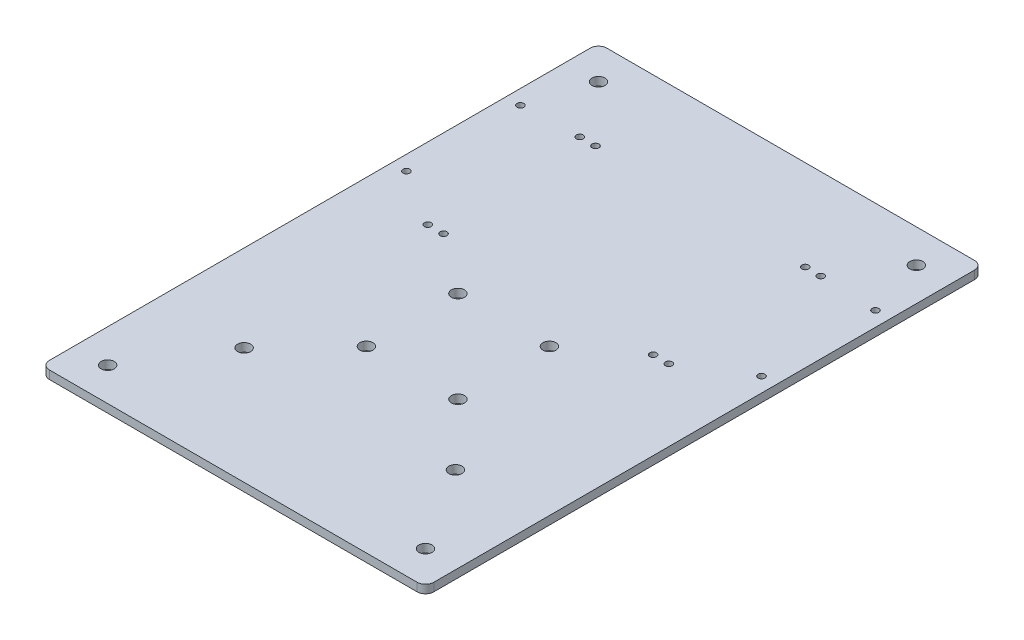
SolidWorks part; units mm, degrees
ref_plane "Front Plane" through (0, 0, 0) normal (0, 0, 1) x (1, 0, 0)
ref_plane "Top Plane" through (0, 0, 0) normal (0, 1, 0) x (1, 0, 0)
ref_plane "Right Plane" through (0, 0, 0) normal (1, 0, 0) x (0, 0, -1)
sketch "Sketch1" plane through (0, 0, 0) normal (0, 1, 0) x (1, 0, 0)
  line L1 (-60.6425, -93.6625) -> (60.6425, -93.6625) construction
  line L2 (-60.6425, -93.6625) -> (-60.6425, 93.6625) construction
  line L3 (-60.6425, 93.6625) -> (60.6425, 93.6625) construction
  line L4 (60.6425, -93.6625) -> (60.6425, 93.6625) construction
  line L5 (-60.6425, -93.6625) -> (60.6425, 93.6625) construction
  line L6 (-60.6425, 93.6625) -> (60.6425, -93.6625) construction
  line L7 (-73.3425, -106.3625) -> (73.3425, -106.3625)
  line L8 (-73.3425, -106.3625) -> (-73.3425, 106.3625)
  line L9 (-73.3425, 106.3625) -> (73.3425, 106.3625)
  line L10 (73.3425, -106.3625) -> (73.3425, 106.3625)
  line L11 (-73.3425, -106.3625) -> (73.3425, 106.3625) construction
  line L12 (-73.3425, 106.3625) -> (73.3425, -106.3625) construction
  circle A0 centre (-60.6425, 93.6625) radius 2.4892
  circle A1 centre (60.6425, 93.6625) radius 2.4892
  circle A2 centre (60.6425, -93.6625) radius 2.4892
  circle A3 centre (-60.6425, -93.6625) radius 2.4892
  point P0 (0, 0)
  point P11 (0, 0)
  dimension "D1" = 4.9784
  dimension "D2" = 121.285
  dimension "D3" = 187.325
  dimension "D4" = 12.7
  dimension "D5" = 12.7
extrude "Boss-Extrude1" add sketch "Sketch1" along normal mid plane 3.175
fillet "Fillet1" radius 3.175 4 edges at (-73.3425, 0, 106.3625) (-73.3425, 0, -106.3625) (73.3425, 0, -106.3625) (73.3425, 0, 106.3625)
sketch "Sketch2" plane through (0, 1.5875, 0) normal (0, 1, 0) x (1, 0, 0)
  line L1 (-46, 13.8625) -> (46, 13.8625) construction
  line L2 (-46, 13.8625) -> (-46, 71.8625) construction
  line L3 (-46, 71.8625) -> (46, 71.8625) construction
  line L4 (46, 13.8625) -> (46, 71.8625) construction
  line L5 (-46, 13.8625) -> (46, 71.8625) construction
  line L6 (-46, 71.8625) -> (46, 13.8625) construction
  line L7 (70.1675, 106.3625) -> (-70.1675, 106.3625) construction
  line L9 (-40, 13.8625) -> (40, 13.8625) construction
  line L10 (-40, 13.8625) -> (-40, 71.8625) construction
  line L11 (-40, 71.8625) -> (40, 71.8625) construction
  line L12 (40, 13.8625) -> (40, 71.8625) construction
  line L13 (-40, 13.8625) -> (40, 71.8625) construction
  line L14 (-40, 71.8625) -> (40, 13.8625) construction
  circle A0 centre (-46, 71.8625) radius 1.3
  circle A1 centre (-46, 13.8625) radius 1.3
  circle A2 centre (46, 71.8625) radius 1.3
  circle A3 centre (46, 13.8625) radius 1.3
  circle A4 centre (-40, 71.8625) radius 1.3
  circle A5 centre (-40, 13.8625) radius 1.3
  circle A6 centre (40, 13.8625) radius 1.3
  circle A7 centre (40, 71.8625) radius 1.3
  point P0 (0, 42.8625)
  point P16 (0, 42.8625)
  dimension "D2" = 2.6
  dimension "D1" = 46
  dimension "D3" = 58
  dimension "D4" = 63.5
  dimension "D5" = 40
extrude "Cut-Extrude1" cut sketch "Sketch2" against normal through all contours A6 | A7 | A0 | A1 | A3 | A2 | A4 | A5
sketch "Sketch3" plane through (0, 1.5875, 0) normal (0, 1, 0) x (1, 0, 0)
  line L0 (70.1675, 106.3625) -> (-70.1675, 106.3625) construction
  line L1 (-67.75, 70.9625) -> (67.75, 70.9625) construction
  line L2 (-67.75, 70.9625) -> (-67.75, 27.4625) construction
  line L3 (-67.75, 27.4625) -> (67.75, 27.4625) construction
  line L4 (67.75, 70.9625) -> (67.75, 27.4625) construction
  line L5 (-67.75, 70.9625) -> (67.75, 27.4625) construction
  line L6 (-67.75, 27.4625) -> (67.75, 70.9625) construction
  circle A0 centre (67.75, 70.9625) radius 1.3
  circle A1 centre (-67.75, 70.9625) radius 1.3
  circle A2 centre (-67.75, 27.4625) radius 1.3
  circle A3 centre (67.75, 27.4625) radius 1.3
  point P0 (0, 49.2125)
  dimension "D3" = 2.6
  dimension "D1" = 135.5
  dimension "D2" = 43.5
  dimension "D4" = 57.15
extrude "Cut-Extrude2" cut sketch "Sketch3" against normal through all
sketch "Sketch4" plane through (0, 1.5875, 0) normal (0, 1, 0) x (1, 0, 0)
  line L0 (40.3225, -61.9125) -> (-40.3225, -61.9125) construction
  line L1 (-70.1675, -106.3625) -> (70.1675, -106.3625) construction
  circle A0 centre (-40.3225, -61.9125) radius 2.4892
  circle A1 centre (40.3225, -61.9125) radius 2.4892
  point P3 (0, -61.9125)
  dimension "D2" = 4.9784
  dimension "D1" = 80.645
  dimension "D3" = 44.45
extrude "Cut-Extrude3" cut sketch "Sketch4" against normal through all
sketch "Sketch5" plane through (0, 1.5875, 0) normal (0, 1, 0) x (1, 0, 0)
  circle A0 centre (17.4625, -38.1) radius 2.4892 construction
  circle A1 centre (17.4625, -3.175) radius 2.4892 construction
  circle A2 centre (-17.4625, -3.175) radius 2.4892 construction
  circle A3 centre (-17.4625, -38.1) radius 2.4892 construction
  circle A4 centre (17.4625, -38.1) radius 2.4892
  circle A5 centre (17.4625, -3.175) radius 2.4892
  circle A6 centre (-17.4625, -3.175) radius 2.4892
  circle A7 centre (-17.4625, -38.1) radius 2.4892
extrude "Cut-Extrude4" cut sketch "Sketch5" against normal up to next
